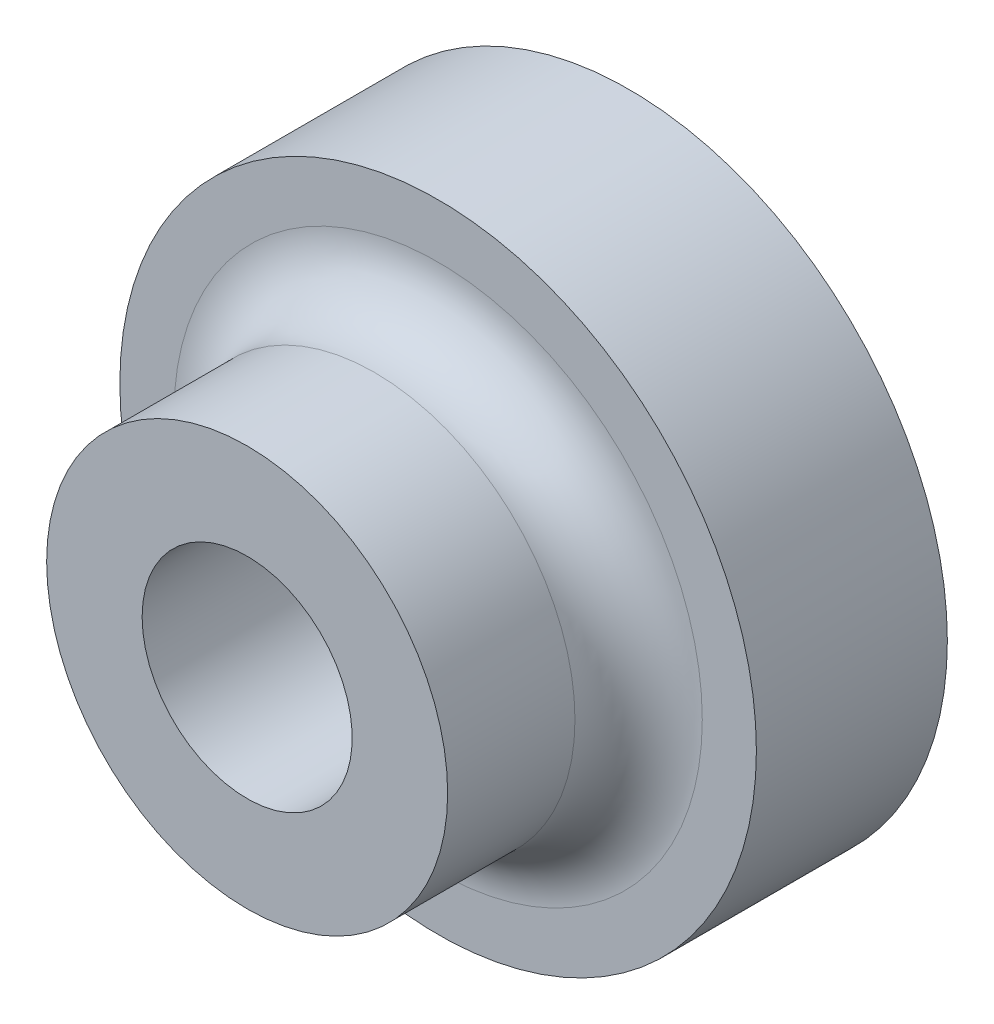
SolidWorks part; units mm, degrees
ref_plane "Plano frontal" through (0, 0, 0) normal (0, 0, 1) x (1, 0, 0)
ref_plane "Plano superior" through (0, 0, 0) normal (0, 1, 0) x (1, 0, 0)
ref_plane "Plano direito" through (0, 0, 0) normal (1, 0, 0) x (0, 0, -1)
sketch "Sketch1" plane through (0, 0, 0) normal (0, 0, 1) x (1, 0, 0)
  circle A0 centre (0, 0) radius 3.15
  dimension "D1" = 6.3
extrude "Boss-Extrude1" add sketch "Sketch1" along normal blind 3
sketch "Sketch2" plane through (0, 0, 0) normal (0, 0, -1) x (-1, 0, 0)
  circle A0 centre (0, 0) radius 5
  dimension "D1" = 10
extrude "Boss-Extrude2" add sketch "Sketch2" along normal blind 3
fillet "Fillet1" radius 1 1 edges at (3.15, 0, 0)
sketch "Sketch3" plane through (0, 0, -3) normal (0, 0, -1) x (-1, 0, 0)
  circle A0 centre (0, 0) radius 1.65
  dimension "D1" = 3.3
extrude "Cut-Extrude1" cut sketch "Sketch3" against normal up to next
sketch "Sketch4" plane through (0, 0, -3) normal (0, 0, -1) x (-1, 0, 0)
  circle A0 centre (0, 0) radius 3
  dimension "D1" = 6
extrude "Cut-Extrude2" cut sketch "Sketch4" against normal blind 2.5
